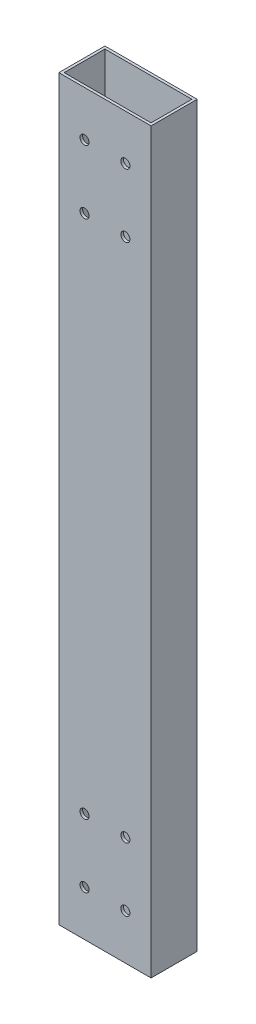
SolidWorks part; units mm, degrees
material "Thornel VCB-20 Carbon Cloth"
ref_plane "Front Plane" through (0, 0, 0) normal (0, 0, 1) x (1, 0, 0)
ref_plane "Top Plane" through (0, 0, 0) normal (0, 1, 0) x (1, 0, 0)
ref_plane "Right Plane" through (0, 0, 0) normal (1, 0, 0) x (0, 0, -1)
sketch "Sketch1" plane through (0, 0, 0) normal (0, 1, 0) x (1, 0, 0)
  line L0 (-25.4, 0) -> (-28.575, 0) construction
  line L1 (-25.4, -12.7) -> (25.4, -12.7)
  line L2 (-25.4, -12.7) -> (-25.4, 12.7)
  line L3 (-25.4, 12.7) -> (25.4, 12.7)
  line L4 (25.4, -12.7) -> (25.4, 12.7)
  line L5 (-25.4, -12.7) -> (25.4, 12.7) construction
  line L6 (-25.4, 12.7) -> (25.4, -12.7) construction
  line L11 (-23.95, 11.25) -> (23.95, 11.25)
  line L12 (23.95, -11.25) -> (23.95, 11.25)
  line L13 (0, -12.7) -> (0, -15.875) construction
  line L14 (-23.95, -11.25) -> (23.95, -11.25)
  line L15 (-23.95, -11.25) -> (-23.95, 11.25)
  point P0 (0, 0)
  point P6 (0, 0)
  dimension "D1" = 25.4
  dimension "D2" = 50.8
  dimension "D3" = 1.45
extrude "Boss-Extrude1" add sketch "Sketch1" along normal blind 406.4
sketch "Sketch2" plane through (0, 0, 12.7) normal (0, 0, 1) x (1, 0, 0)
  line L1 (-11.25, 25) -> (11.25, 25) construction
  line L2 (-11.25, 25) -> (-11.25, 60) construction
  line L3 (-11.25, 60) -> (11.25, 60) construction
  line L4 (11.25, 25) -> (11.25, 60) construction
  circle A0 centre (-11.25, 60) radius 2.5
  circle A1 centre (-11.25, 25) radius 2.5
  circle A2 centre (11.25, 25) radius 2.5
  circle A3 centre (11.25, 60) radius 2.5
  point P4 (0, 25)
  dimension "D4" = 5
  dimension "D1" = 22.5
  dimension "D2" = 35
  dimension "D3" = 25
extrude "Cut-Extrude1" cut sketch "Sketch2" against normal through all contours A3 | A0 | A1 | A2
ref_plane "Plane1" through (0, 203.2, 0) normal (0, 1, 0) x (1, 0, 0)
mirror "Mirror1" about plane through (0, 203.2, 0) normal (0, 1, 0) of "Cut-Extrude1"
equation "\"tube_width\"= 1in"
equation "\"tube_height\"= 2in"
equation "\"tube_thickness\"= 0.125in"
equation "\"tube_length\"= 1.5ft"
equation "\"D1@Boss-Extrude1\"=\"tube_length\""
equation "\"D1@Sketch1\"=\"tube_width\""
equation "\"D2@Sketch1\"=\"tube_height\""
